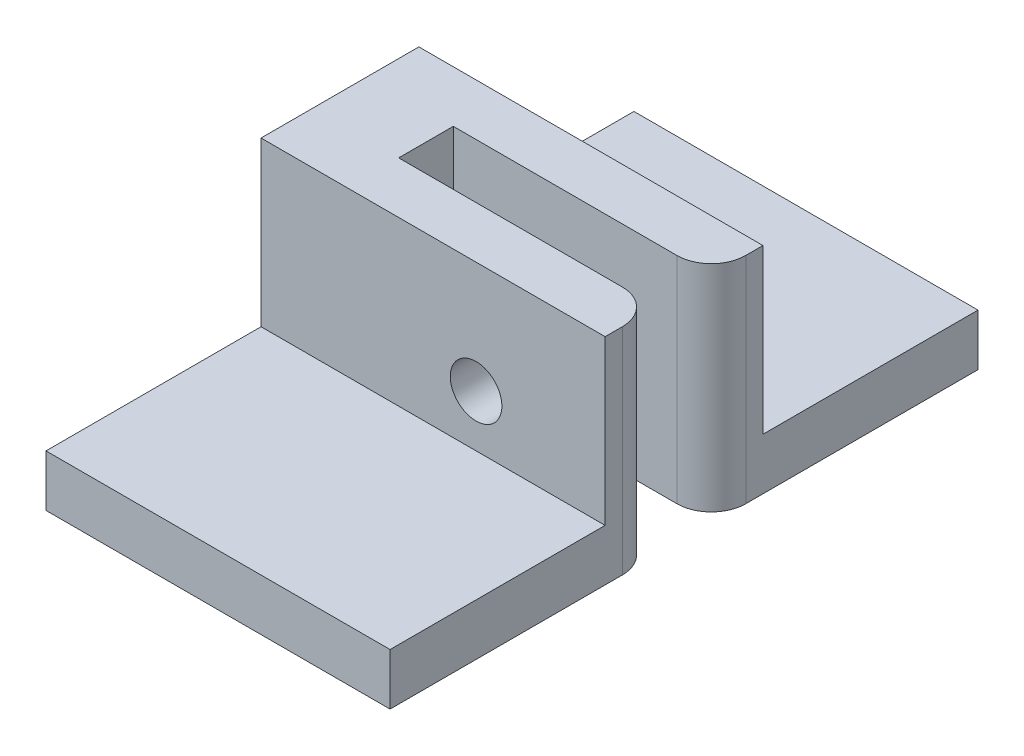
SolidWorks part; units mm, degrees
ref_plane "Front Plane" through (0, 0, 0) normal (0, 0, 1) x (1, 0, 0)
ref_plane "Top Plane" through (0, 0, 0) normal (0, 1, 0) x (1, 0, 0)
ref_plane "Right Plane" through (0, 0, 0) normal (1, 0, 0) x (0, 0, -1)
sketch "Sketch1" plane through (0, 0, 0) normal (1, 0, 0) x (0, 0, -1)
  line L0 (0, 12.5) -> (3, 12.5)
  line L1 (0, 0) -> (-3.175, 0)
  line L2 (0, 0) -> (0, 12.5) construction
  line L3 (0, 12.5) -> (-3.175, 12.5)
  line L4 (-3.175, 0) -> (-3.175, 12.5) construction
  line L5 (3, 12.5) -> (3, 3)
  line L6 (3, 3) -> (15.5, 3)
  line L7 (15.5, 3) -> (15.5, 0)
  line L8 (15.5, 0) -> (0, 0)
  line L9 (-1.5875, 12.5) -> (-1.5875, 0) construction
  line L10 (-18.675, 0) -> (-3.175, 0)
  line L11 (-18.675, 3) -> (-18.675, 0)
  line L12 (-6.175, 3) -> (-18.675, 3)
  line L13 (-6.175, 12.5) -> (-6.175, 3)
  line L14 (-3.175, 12.5) -> (-6.175, 12.5)
  dimension "D1" = 3.175
  dimension "D2" = 12.5
  dimension "D3" = 3
  dimension "D4" = 3
  dimension "D5" = 12.5
extrude "Boss-Extrude1" add sketch "Sketch1" along normal blind 20
sketch "Sketch2" plane through (20, 0, 0) normal (1, 0, 0) x (0, 0, -1)
  line L0 (-1.5875, 12.5) -> (-1.5875, 0) construction
  line L1 (3, 12.5) -> (-6.175, 12.5) construction
  line L2 (-18.675, 0) -> (15.5, 0) construction
  line L4 (-3.175, 12.5) -> (0, 12.5)
  line L5 (-3.175, 12.5) -> (-3.175, 0)
  line L6 (-3.175, 0) -> (0, 0)
  line L7 (0, 12.5) -> (0, 0)
  line L8 (-3.175, 12.5) -> (0, 0) construction
  line L9 (-3.175, 0) -> (0, 12.5) construction
  point P6 (-1.5875, 6.25)
extrude "Cut-Extrude1" cut sketch "Sketch2" against normal blind 15
sketch "Sketch3" plane through (0, 0, 6.175) normal (0, 0, 1) x (1, 0, 0)
  line L0 (5, 12.5) -> (5, 3) construction
  line L1 (20, 12.5) -> (0, 12.5) construction
  line L2 (20, 3) -> (0, 3) construction
  line L3 (0, 12.5) -> (0, 3) construction
  line L4 (5, 6) -> (20, 6) construction
  line L5 (20, 12.5) -> (20, 3) construction
  line L6 (20, 0) -> (0, 0) construction
  circle A0 centre (12.5, 6) radius 1.5
  dimension "D2" = 3
  dimension "D1" = 5
  dimension "D3" = 6
extrude "Cut-Extrude2" cut sketch "Sketch3" against normal through all
fillet "Fillet1" radius 2 2 edges at (20, 6.25, 3.175) (20, 6.25, 0)
